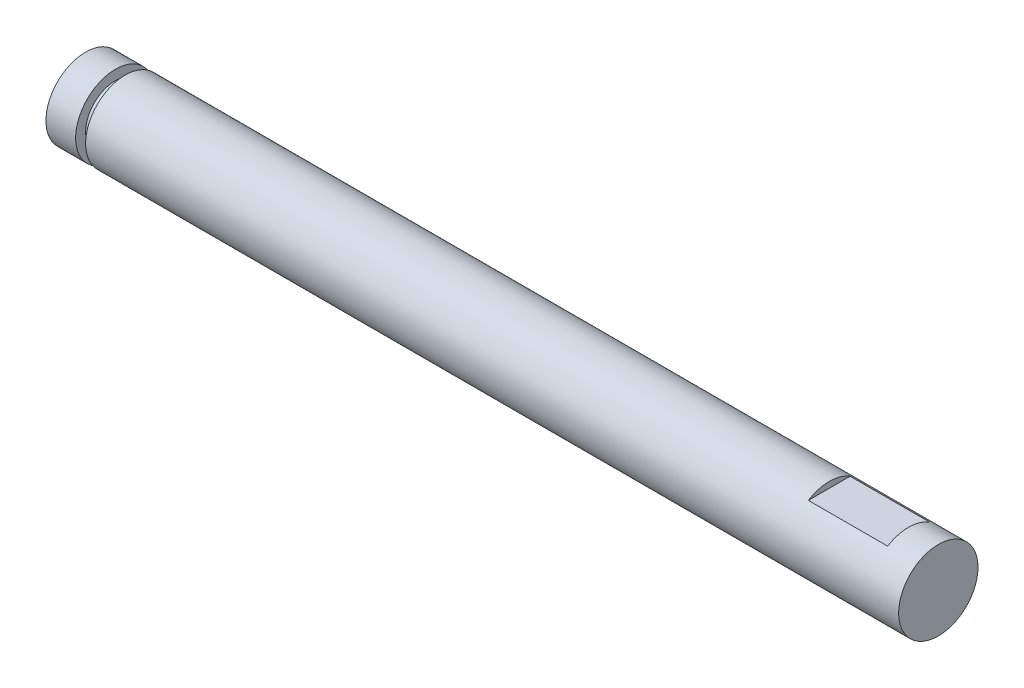
SolidWorks part; units mm, degrees
ref_plane "Front Plane" through (0, 0, 0) normal (0, 0, 1) x (1, 0, 0)
ref_plane "Top Plane" through (0, 0, 0) normal (0, 1, 0) x (1, 0, 0)
ref_plane "Right Plane" through (0, 0, 0) normal (1, 0, 0) x (0, 0, -1)
sketch "Sketch1" plane through (0, 0, 0) normal (0, 0, 1) x (1, 0, 0)
  line L0 (21.5, 0) -> (-21.5, 0)
  line L1 (21.5, 0) -> (21.5, 2)
  line L2 (21.5, 2) -> (-19.5, 2)
  line L3 (-21.5, 2) -> (-21.5, 0)
  line L4 (-21.5, 0) -> (-32.2413, 0) construction
  line L5 (-20, 2) -> (-20, 1.5)
  line L6 (-20, 1.5) -> (-19.5, 1.5)
  line L7 (-19.5, 1.5) -> (-19.5, 2)
  line L8 (-20, 2) -> (-21.5, 2)
  dimension "D1" = 4
  dimension "D2" = 43
  dimension "D3" = 0.5
  dimension "D4" = 0.5
  dimension "D5" = 1.5
revolve "Revolve1" add sketch "Sketch1" angle 360 about L4
sketch "Sketch2" plane through (0, 0, 0) normal (0, 1, 0) x (1, 0, 0)
  line L0 (0, 0) -> (36.2818, 0) construction
  line L1 (16, 2) -> (20, 2)
  line L2 (16, 2) -> (16, -2)
  line L3 (16, -2) -> (20, -2)
  line L4 (20, 2) -> (20, -2)
  line L5 (21.5, -2) -> (21.5, 2) construction
  dimension "D1" = 1.5
  dimension "D2" = 4
  dimension "D3" = 4
extrude "Cut-Extrude1" cut sketch "Sketch2" against normal blind 0.3 from offset 2
